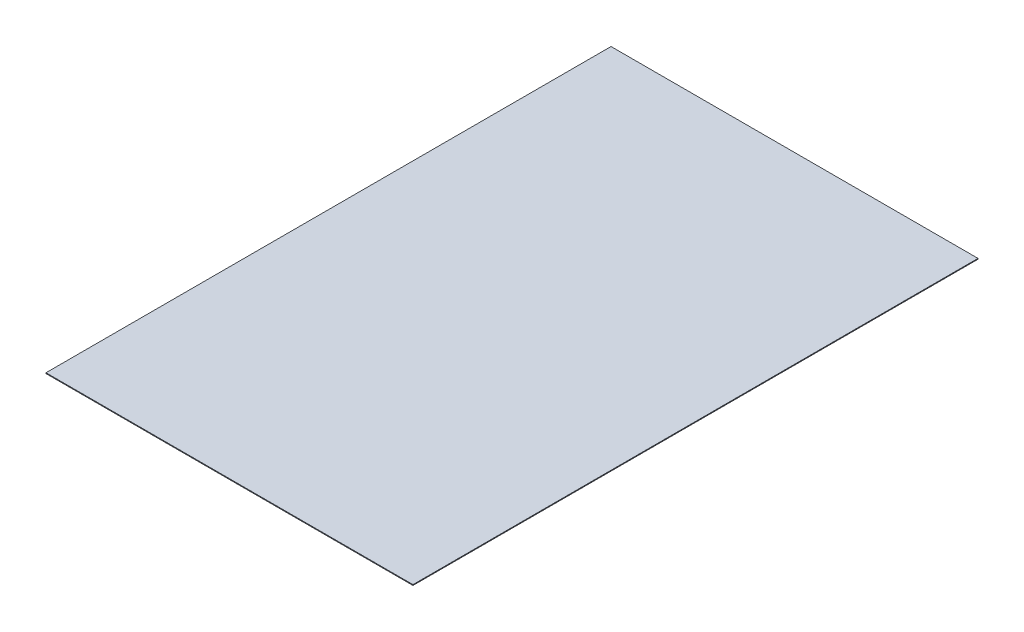
SolidWorks part; units mm, degrees
ref_plane "Front Plane" through (0, 0, 0) normal (0, 0, 1) x (1, 0, 0)
ref_plane "Top Plane" through (0, 0, 0) normal (0, 1, 0) x (1, 0, 0)
ref_plane "Right Plane" through (0, 0, 0) normal (1, 0, 0) x (0, 0, -1)
sketch "Sketch1" plane through (0, 0, 0) normal (0, 1, 0) x (1, 0, 0)
  line L1 (0, 0) -> (239, 0)
  line L2 (0, 0) -> (0, 368)
  line L3 (0, 368) -> (239, 368)
  line L4 (239, 0) -> (239, 368)
  dimension "D1" = 239
  dimension "D2" = 368
extrude "Boss-Extrude1" add sketch "Sketch1" along normal blind 0.5
